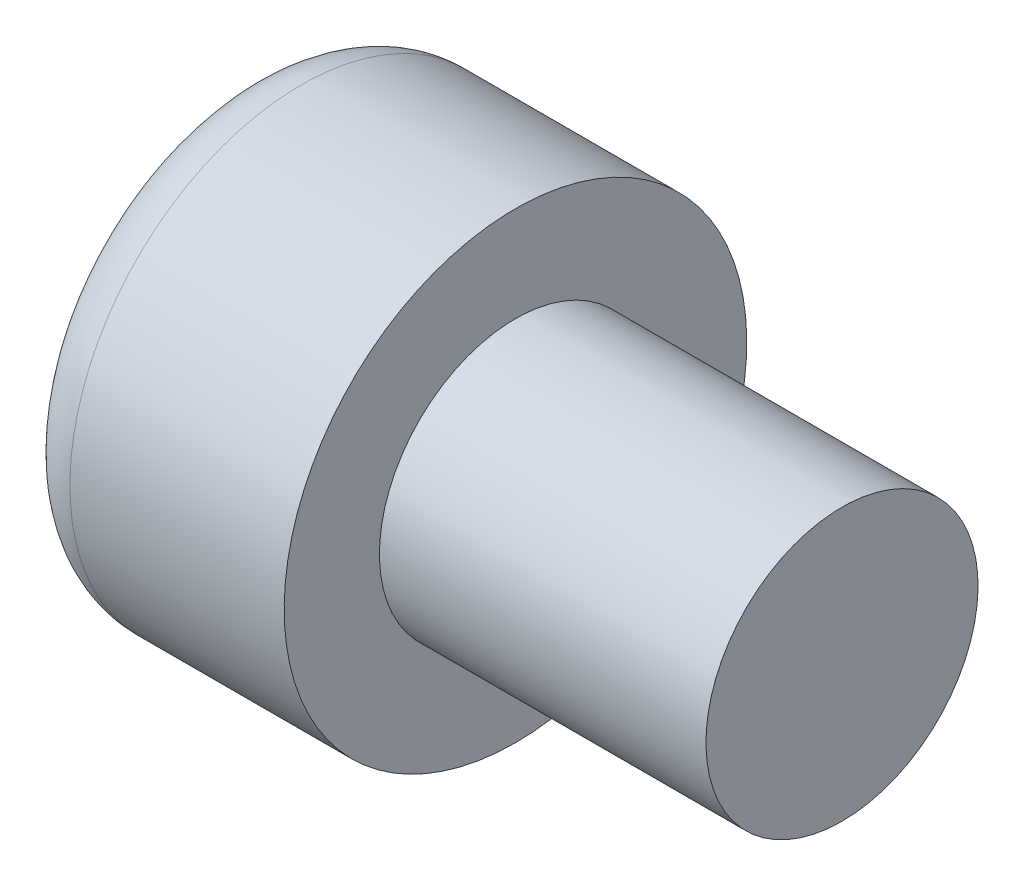
SolidWorks part; units mm, degrees
material "Plain Carbon Steel"
ref_plane "Front Plane" through (0, 0, 0) normal (0, 0, 1) x (1, 0, 0)
ref_plane "Top Plane" through (0, 0, 0) normal (0, 1, 0) x (1, 0, 0)
ref_plane "Right Plane" through (0, 0, 0) normal (1, 0, 0) x (0, 0, -1)
sketch "Sketch1" plane through (0, 0, 0) normal (0, 0, 1) x (1, 0, 0)
  line L0 (0, 0) -> (0, 3.1875)
  line L1 (1.0625, 4.25) -> (5, 4.25)
  line L2 (5, 4.25) -> (5, 2.5)
  line L3 (5, 2.5) -> (11, 2.5)
  line L4 (11, 2.5) -> (11, 0)
  line L5 (11, 0) -> (0, 0) construction
  line L6 (1.0625, 3.1875) -> (1.0625, 2.125) construction
  line L7 (1.0625, 2.125) -> (1.0625, 1.0625) construction
  line L8 (1.0625, 1.0625) -> (1.0625, 0) construction
  line L9 (1.0625, 4.25) -> (1.0625, 3.1875) construction
  line L10 (0, 0) -> (11, 0)
  arc A0 (0, 3.1875) -> (1.0625, 4.25) centre (1.0625, 3.1875) cw
  dimension "D1" = 5
  dimension "D2" = 8.5
  dimension "D3" = 5
  dimension "D4" = 6
revolve "Revolve1" add sketch "Sketch1" angle 360 about L10
sketch "Sketch2" plane through (0, 0, 0) normal (-1, 0, 0) x (0, 0, 1)
  line L1 (0, 2.3094) -> (-2, 1.1547)
  line L2 (-2, 1.1547) -> (-2, -1.1547)
  line L3 (-2, -1.1547) -> (0, -2.3094)
  line L4 (0, -2.3094) -> (2, -1.1547)
  line L5 (2, -1.1547) -> (2, 1.1547)
  line L6 (2, 1.1547) -> (0, 2.3094)
  circle A0 centre (0, 0) radius 2 construction
  dimension "D1" = 4
extrude "Cut-Extrude1" cut sketch "Sketch2" against normal blind 2.5
